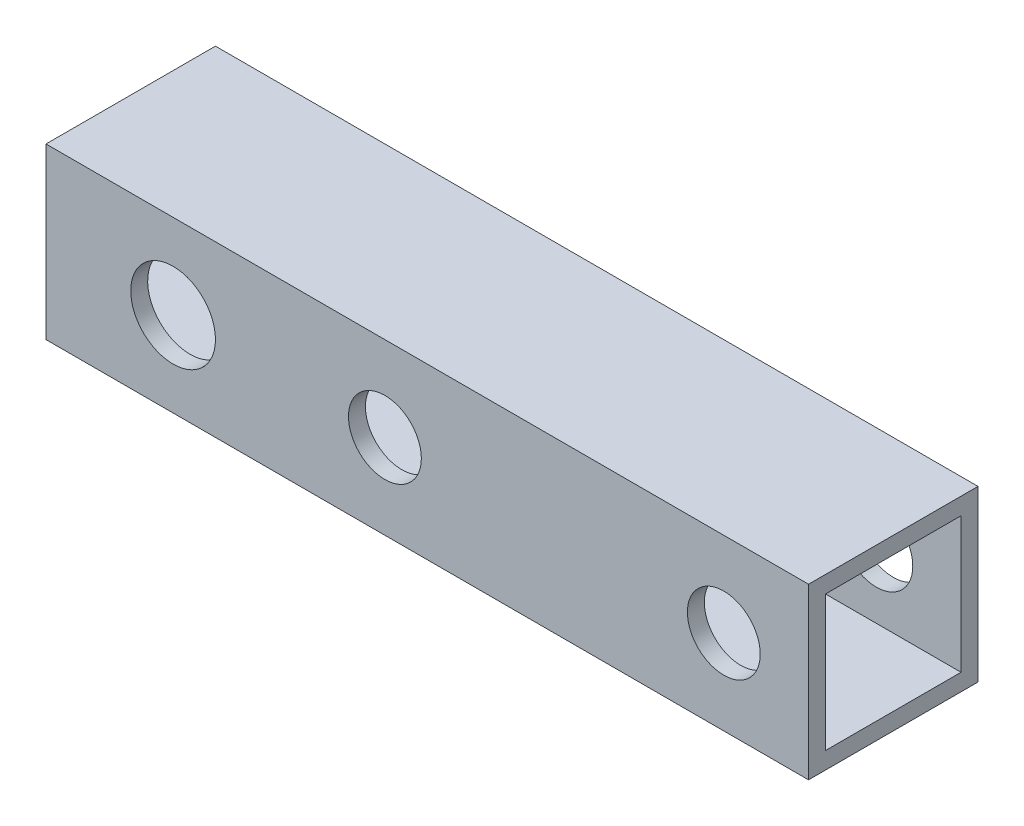
SolidWorks part; units mm, degrees
material "5052-H34"
ref_plane "正面" through (0, 0, 0) normal (0, 0, 1) x (1, 0, 0)
ref_plane "平面" through (0, 0, 0) normal (0, 1, 0) x (1, 0, 0)
ref_plane "右側面" through (0, 0, 0) normal (1, 0, 0) x (0, 0, -1)
sketch "ｽｹｯﾁ1" plane through (0, 0, 0) normal (1, 0, 0) x (0, 0, -1)
  line L1 (-5, 5) -> (5, 5)
  line L2 (-5, 5) -> (-5, -5)
  line L3 (-5, -5) -> (5, -5)
  line L4 (5, 5) -> (5, -5)
  line L5 (-5, 5) -> (5, -5) construction
  line L6 (-5, -5) -> (5, 5) construction
  point P0 (0, 0)
  dimension "D1" = 10
  dimension "D2" = 10
extrude "押し出し-薄板1" add sketch "ｽｹｯﾁ1" along normal blind 45 thin
sketch "ｽｹｯﾁ2" plane through (0, 0, 5) normal (0, 0, 1) x (1, 0, 0)
  line L0 (22.5, 5) -> (22.5, -5) construction
  line L1 (45, 5) -> (0, 5) construction
  line L2 (45, -5) -> (0, -5) construction
  line L3 (45, 0) -> (7.5, 0) construction
  line L4 (45, 5) -> (45, -5) construction
  circle A0 centre (40, 0) radius 2.15
  circle A1 centre (20, 0) radius 2.15
  circle A2 centre (7.5, 0) radius 2.5
  dimension "D2" = 5
  dimension "D3" = 4.3
  dimension "D1" = 37.5
  dimension "D4" = 5
  dimension "D5" = 20
extrude "ｶｯﾄ - 押し出し1" cut sketch "ｽｹｯﾁ2" against normal through all
